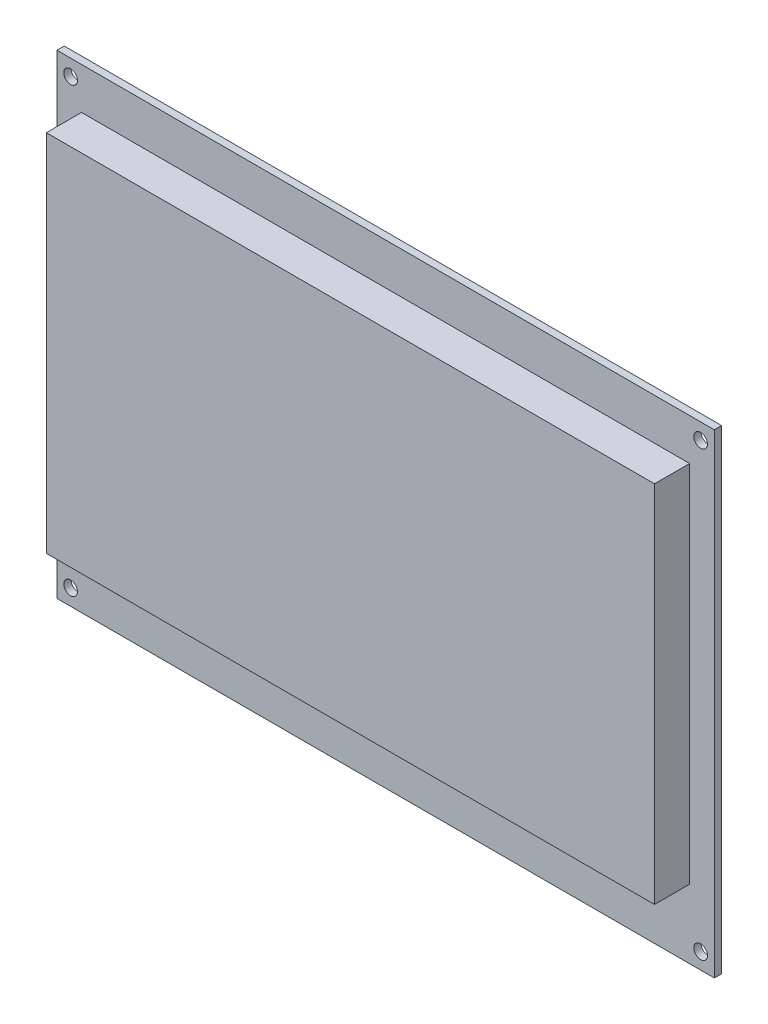
SolidWorks part; units mm, degrees
ref_plane "前视基准面" through (0, 0, 0) normal (0, 0, 1) x (1, 0, 0)
ref_plane "上视基准面" through (0, 0, 0) normal (0, 1, 0) x (1, 0, 0)
ref_plane "右视基准面" through (0, 0, 0) normal (1, 0, 0) x (0, 0, -1)
sketch "草图1" plane through (0, 0, 0) normal (0, 0, 1) x (1, 0, 0)
  line L0 (-72, -52) -> (72, -52)
  line L1 (72, -52) -> (72, 52)
  line L2 (72, 52) -> (-72, 52)
  line L3 (-66.6, -36.9) -> (66.6, -36.9)
  line L4 (66.6, -36.9) -> (66.6, 42.9)
  line L5 (66.6, 42.9) -> (-66.6, 42.9)
  line L6 (-66.6, 42.9) -> (-66.6, -36.9)
  line L7 (-72, 52) -> (-72, -52)
  line L8 (-114.9708, 0) -> (137.3987, 0) construction
  line L9 (0, -98.8356) -> (0, 73.1329) construction
  circle A0 centre (-69, 48.5) radius 1.5
  circle A1 centre (69, 48.5) radius 1.5
  circle A2 centre (-69, -48.5) radius 1.5
  circle A3 centre (69, -48.5) radius 1.5
  dimension "D1" = 144
  dimension "D2" = 104
  dimension "D3" = 79.8
  dimension "D4" = 15.1
  dimension "D5" = 97
  dimension "D6" = 97
  dimension "D7" = 138
extrude "拉伸1" add sketch "草图1" along normal blind 1.6 contours L7 L0 L1 L2 A2 A0 L3 L6 L5 L4 A1 A3
sketch "草图2" plane through (0, 0, 0) normal (0, 0, -1) x (-1, 0, 0)
  line L0 (66.6, -36.9) -> (66.6, 42.9) construction
  line L1 (-66.6, -36.9) -> (66.6, -36.9) construction
  line L2 (-66.6, 42.9) -> (-66.6, -36.9) construction
  line L3 (66.6, 42.9) -> (-66.6, 42.9) construction
  line L4 (66.6, -36.9) -> (66.6, 42.9)
  line L5 (-66.6, -36.9) -> (66.6, -36.9)
  line L6 (-66.6, 42.9) -> (-66.6, -36.9)
  line L7 (66.6, 42.9) -> (-66.6, 42.9)
extrude "拉伸2" add sketch "草图2" against normal blind 9.3
